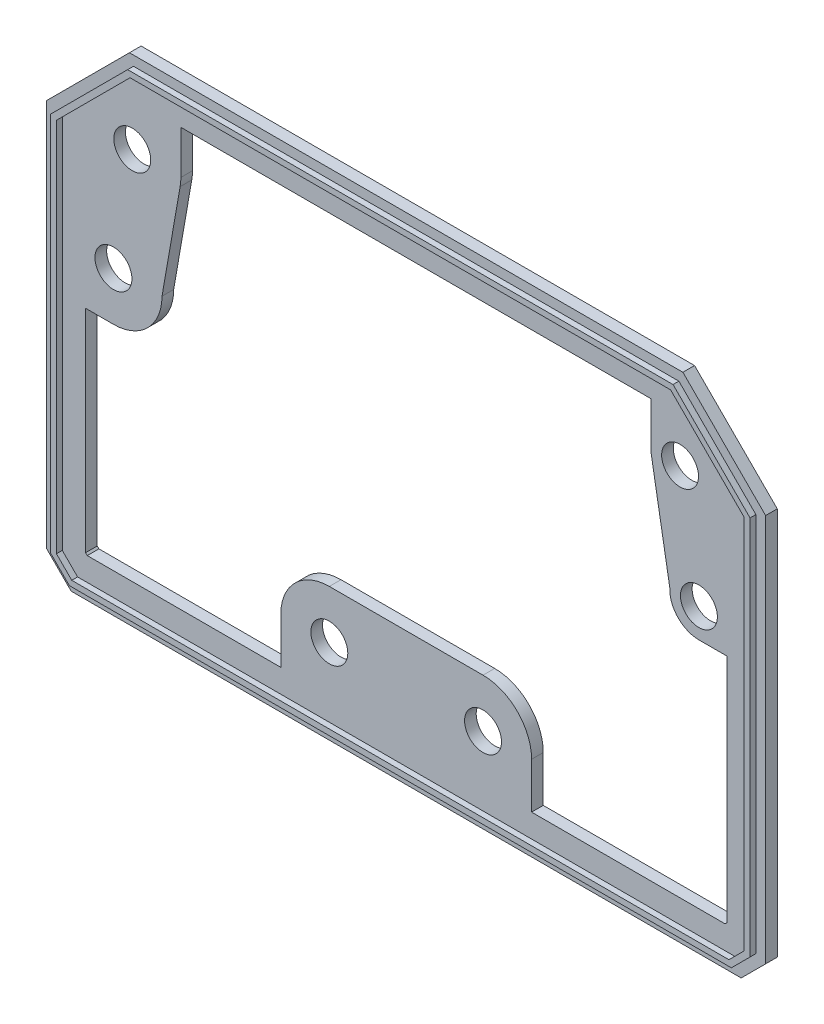
SolidWorks part; units mm, degrees
ref_plane "Front Plane" through (0, 0, 0) normal (0, 0, 1) x (1, 0, 0)
ref_plane "Top Plane" through (0, 0, 0) normal (0, 1, 0) x (1, 0, 0)
ref_plane "Right Plane" through (0, 0, 0) normal (1, 0, 0) x (0, 0, -1)
sketch "Sketch1" plane through (0, 0, 0) normal (0, 0, 1) x (1, 0, 0)
  line L8 (-68, 2.5147) -> (-65.4853, 0)
  line L10 (-68, 2.5147) -> (-65.4853, 0)
  line L12 (-65.4853, 0) -> (3.4853, 0)
  line L14 (-65.4853, 0) -> (3.4853, 0)
  line L32 (2, 27.9646) -> (-0.8657, 27.9646)
  line L33 (2, 27.9646) -> (-0.8657, 27.9646)
  line L34 (2, 4.1716) -> (2, 27.9646)
  line L36 (-18.0902, 4) -> (1.8284, 4)
  line L37 (-18.0902, 8.7108) -> (-18.0902, 4)
  line L38 (-38.9098, 13.7108) -> (-23.0902, 13.7108)
  line L39 (-43.9098, 4) -> (-43.9098, 8.7108)
  line L40 (-63.8284, 4) -> (-43.9098, 4)
  line L42 (-64, 25.9646) -> (-64, 4.1716)
  line L43 (-61.1343, 25.9646) -> (-64, 25.9646)
  line L44 (-54.2697, 41.6693) -> (-56.1343, 30.9646)
  line L45 (-54.1956, 47) -> (-54.1956, 42.5273)
  line L46 (-5.8044, 47) -> (-54.1956, 47)
  line L47 (-5.8044, 42.5273) -> (-5.8044, 47)
  line L50 (2, 4.1716) -> (2, 27.9646)
  line L52 (-18.0902, 4) -> (1.8284, 4)
  line L53 (-18.0902, 8.7108) -> (-18.0902, 4)
  line L54 (-38.9098, 13.7108) -> (-23.0902, 13.7108)
  line L55 (-43.9098, 4) -> (-43.9098, 8.7108)
  line L56 (-63.8284, 4) -> (-43.9098, 4)
  line L58 (-64, 25.9646) -> (-64, 4.1716)
  line L59 (-61.1343, 25.9646) -> (-64, 25.9646)
  line L60 (-54.2697, 41.6693) -> (-56.1343, 30.9646)
  line L61 (-54.1956, 47) -> (-54.1956, 42.5273)
  line L62 (-5.8044, 47) -> (-54.1956, 47)
  line L110 (3.4853, 0) -> (6, 2.5147)
  line L112 (-5.8044, 42.5273) -> (-5.8044, 47)
  line L113 (-3.8619, 31.1156) -> (-5.7599, 42.0125)
  line L114 (-3.8619, 31.1156) -> (-5.7599, 42.0125)
  line L115 (3.4853, 0) -> (6, 2.5147)
  line L165 (6, 2.5147) -> (6, 42.4853)
  line L166 (6, 2.5147) -> (6, 42.4853)
  line L167 (6, 42.4853) -> (-2.5147, 51)
  line L168 (6, 42.4853) -> (-2.5147, 51)
  line L169 (-2.5147, 51) -> (-59.4853, 51)
  line L170 (-2.5147, 51) -> (-59.4853, 51)
  line L171 (-59.4853, 51) -> (-68, 42.4853)
  line L172 (-59.4853, 51) -> (-68, 42.4853)
  line L173 (-68, 42.4853) -> (-68, 2.5147)
  line L174 (-68, 42.4853) -> (-68, 2.5147)
  line L183 (1.8284, 4) -> (2, 4.1716)
  line L184 (1.8284, 4) -> (2, 4.1716)
  line L185 (-64, 4.1716) -> (-63.8284, 4)
  line L186 (-64, 4.1716) -> (-63.8284, 4)
  circle A1 centre (-0.8657, 30.9646) radius 1.9
  circle A2 centre (-0.8657, 30.9646) radius 1.9
  circle A3 centre (-61.1343, 30.9646) radius 1.9
  circle A4 centre (-61.1343, 30.9646) radius 1.9
  circle A5 centre (-38.9098, 8.7108) radius 1.9
  arc A6 (-5.8044, 42.5273) -> (-5.7599, 42.0125) centre (-2.8044, 42.5273) ccw
  arc A7 (-18.0902, 8.7108) -> (-23.0902, 13.7108) centre (-23.0902, 8.7108) ccw
  arc A8 (-38.9098, 13.7108) -> (-43.9098, 8.7108) centre (-38.9098, 8.7108) ccw
  arc A9 (-61.1343, 25.9646) -> (-56.1343, 30.9646) centre (-61.1343, 30.9646) ccw
  arc A10 (-54.2697, 41.6693) -> (-54.1956, 42.5273) centre (-59.1956, 42.5273) ccw
  arc A11 (-5.8044, 42.5273) -> (-5.7599, 42.0125) centre (-2.8044, 42.5273) ccw
  arc A13 (-18.0902, 8.7108) -> (-23.0902, 13.7108) centre (-23.0902, 8.7108) ccw
  arc A14 (-38.9098, 13.7108) -> (-43.9098, 8.7108) centre (-38.9098, 8.7108) ccw
  arc A15 (-61.1343, 25.9646) -> (-56.1343, 30.9646) centre (-61.1343, 30.9646) ccw
  arc A16 (-54.2697, 41.6693) -> (-54.1956, 42.5273) centre (-59.1956, 42.5273) ccw
  circle A18 centre (-38.9098, 8.7108) radius 1.9
  circle A19 centre (-23.0902, 8.7108) radius 1.9
  circle A20 centre (-23.0902, 8.7108) radius 1.9
  circle A21 centre (-2.8044, 42.5273) radius 1.9
  circle A22 centre (-2.8044, 42.5273) radius 1.9
  circle A23 centre (-59.1956, 42.5273) radius 1.9
  circle A24 centre (-59.1956, 42.5273) radius 1.9
  arc A48 (-3.8619, 31.1156) -> (-0.8657, 27.9646) centre (-0.8657, 30.9646) ccw
  arc A49 (-3.8619, 31.1156) -> (-0.8657, 27.9646) centre (-0.8657, 30.9646) ccw
  dimension "D1" = 0
  dimension "D2" = 0
  dimension "D3" = 0
  dimension "D4" = 0
  dimension "D5" = 0
  dimension "D6" = 0
  dimension "D7" = 0
  dimension "D8" = 0
extrude "Boss-Extrude1" add sketch "Sketch1" along normal blind 1.2
sketch "Sketch2" plane through (0, 0, 1.2) normal (0, 0, 1) x (1, 0, 0)
  line L8 (-66.4, 41.8225) -> (-66.4, 3.1775)
  line L9 (-66.4, 3.1775) -> (-64.8225, 1.6)
  line L10 (-64.8225, 1.6) -> (2.8225, 1.6)
  line L11 (2.8225, 1.6) -> (4.4, 3.1775)
  line L12 (4.4, 3.1775) -> (4.4, 41.8225)
  line L13 (4.4, 41.8225) -> (-3.1775, 49.4)
  line L14 (-3.1775, 49.4) -> (-58.8225, 49.4)
  line L15 (-58.8225, 49.4) -> (-66.4, 41.8225)
  line L24 (-67, 42.0711) -> (-67, 2.9289)
  line L25 (-67, 2.9289) -> (-65.0711, 1)
  line L26 (-65.0711, 1) -> (3.0711, 1)
  line L27 (3.0711, 1) -> (5, 2.9289)
  line L28 (5, 2.9289) -> (5, 42.0711)
  line L29 (5, 42.0711) -> (-2.9289, 50)
  line L30 (-2.9289, 50) -> (-59.0711, 50)
  line L31 (-59.0711, 50) -> (-67, 42.0711)
  dimension "D2" = 0.6
extrude "Boss-Extrude2" add sketch "Sketch2" along normal blind 0.6
